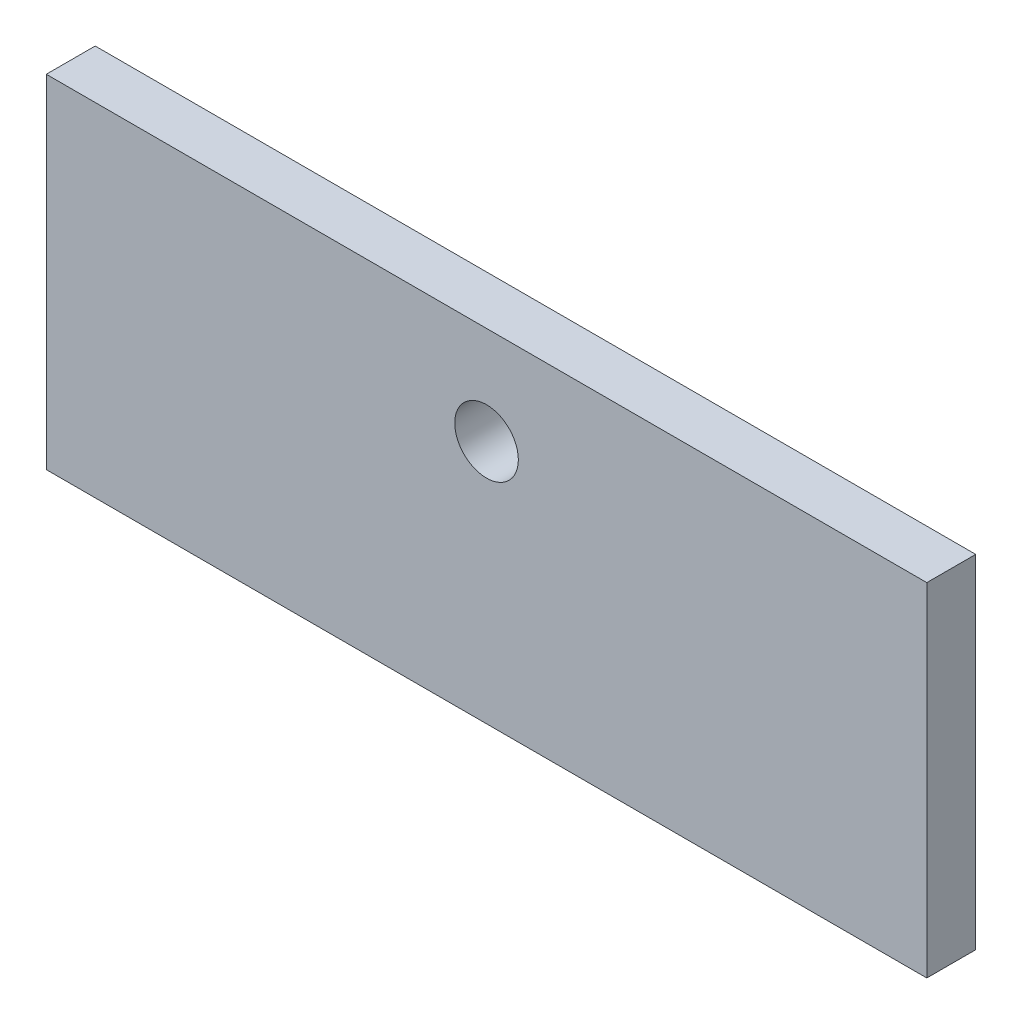
SolidWorks part; units mm, degrees
ref_plane "前视基准面" through (0, 0, 0) normal (0, 0, 1) x (1, 0, 0)
ref_plane "上视基准面" through (0, 0, 0) normal (0, 1, 0) x (1, 0, 0)
ref_plane "右视基准面" through (0, 0, 0) normal (1, 0, 0) x (0, 0, -1)
other "Configuration Table"
sketch "草图1" plane through (0, 0, 0) normal (0, 0, 1) x (1, 0, 0)
  line L0 (0, 0) -> (90, 0)
  line L1 (0, 0) -> (0, 35)
  line L2 (0, 35) -> (90, 35)
  line L3 (90, 35) -> (90, 0)
  line L4 (45, 35) -> (45, 0) construction
  circle A1 centre (45, 25) radius 3.25
  dimension "D3" = 6.5
  dimension "D1" = 90
  dimension "D2" = 35
  dimension "D4" = 10
extrude "凸台-拉伸1" add sketch "草图1" along normal blind 5
